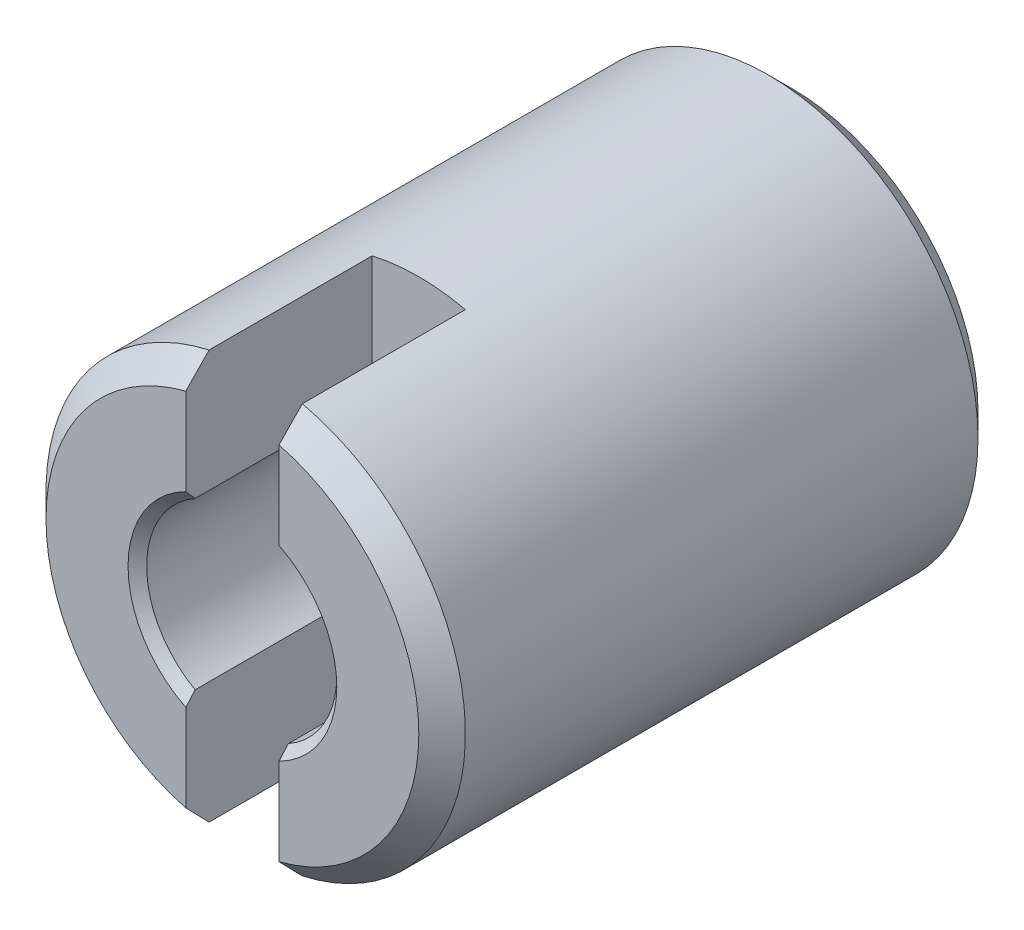
SolidWorks part; units mm, degrees
material "Ст 3 сп 5 ГОСТ 380-94"
ref_plane "Спереди" through (0, 0, 0) normal (0, 0, 1) x (1, 0, 0)
ref_plane "Сверху" through (0, 0, 0) normal (0, 1, 0) x (1, 0, 0)
ref_plane "Справа" through (0, 0, 0) normal (1, 0, 0) x (0, 0, -1)
sketch "Эскиз1" plane through (0, 0, 0) normal (0, 0, 1) x (1, 0, 0)
  circle A0 centre (0, 0) radius 2.25
extrude "Бобышка-Вытянуть1" add sketch "Эскиз1" along normal blind 6
cosmetic thread "Условное изображение резьбы1" parameters "D2"=3.959
sketch "Эскиз2" plane through (0, 0, 6) normal (0, 0, 1) x (1, 0, 0)
  circle A0 centre (0, 0) radius 1.02
extrude "Вырез-Вытянуть1" cut sketch "Эскиз2" against normal blind 6
cosmetic thread "Условное изображение резьбы2" parameters "D2"=2.5
sketch "Эскиз3" plane through (0, 0, 6) normal (0, 0, 1) x (1, 0, 0)
  line L0 (0, 0) -> (0, 3.6286) construction
  line L2 (0.5, -2.5) -> (-0.5, -2.5)
  line L3 (0.5, -2.5) -> (0.5, 2.5)
  line L4 (0.5, 2.5) -> (-0.5, 2.5)
  line L5 (-0.5, -2.5) -> (-0.5, 2.5)
  line L6 (0.5, -2.5) -> (-0.5, 2.5) construction
  line L7 (0.5, 2.5) -> (-0.5, -2.5) construction
  point P1 (0, 0)
  dimension "D1" = 5
  dimension "D2" = 1
extrude "Вырез-Вытянуть2" cut sketch "Эскиз3" against normal blind 2
chamfer "Фаска1" distance 0.25 angle 45 1 edges at (2.25, 0, 6)
chamfer "Фаска2" distance 0.25 angle 45 1 edges at (-2.25, 0, 6)
chamfer "Фаска4" distance 0.25 angle 45 1 edges at (2.25, 0, 0)
chamfer "Фаска5" distance 0.1 angle 45 1 edges at (1.02, 0, 0)
chamfer "Фаска6" distance 0.1 angle 45 1 edges at (1.02, 0, 6)
chamfer "Фаска7" distance 0.1 angle 45 1 edges at (-1.02, 0, 6)
